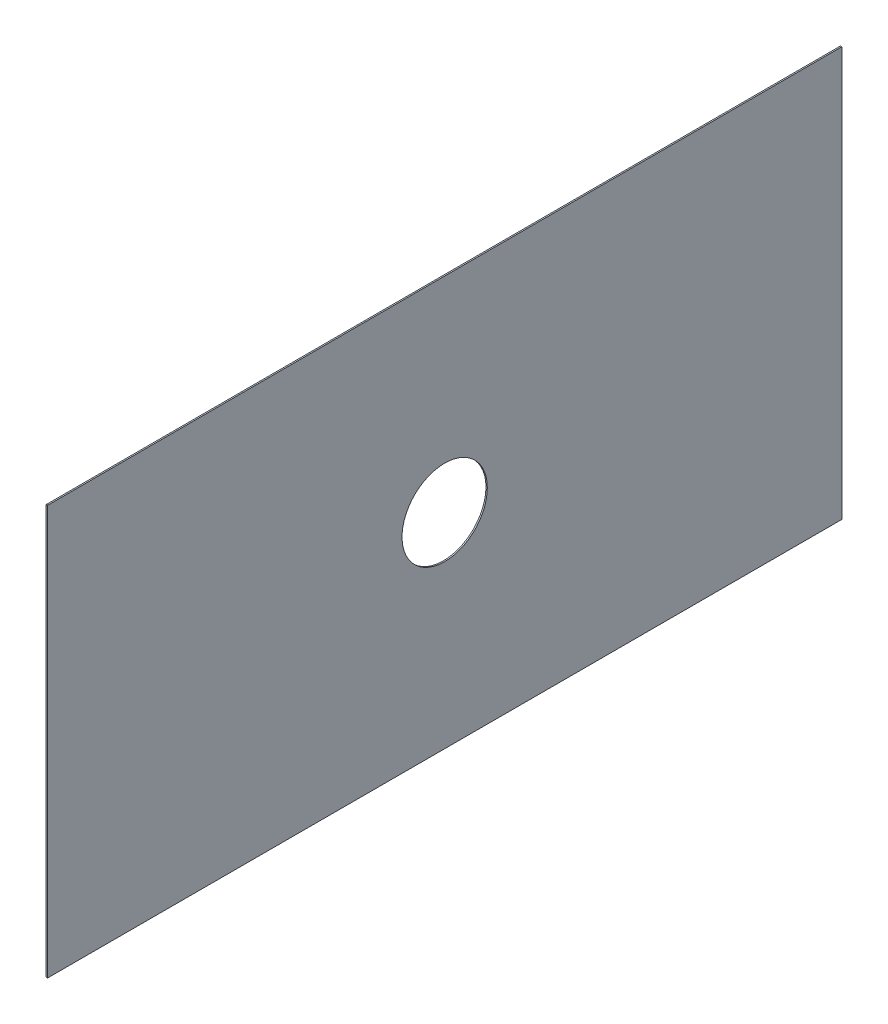
SolidWorks part; units mm, degrees
ref_plane "Alzado" through (0, 0, 0) normal (0, 0, 1) x (1, 0, 0)
ref_plane "Planta" through (0, 0, 0) normal (0, 1, 0) x (1, 0, 0)
ref_plane "Vista lateral" through (0, 0, 0) normal (1, 0, 0) x (0, 0, -1)
sketch "Croquis1" plane through (0, 0, 0) normal (1, 0, 0) x (0, 0, -1)
  line L1 (582, -300) -> (-582, -300)
  line L2 (582, -300) -> (582, 300)
  line L3 (582, 300) -> (-582, 300)
  line L4 (-582, -300) -> (-582, 300)
  line L5 (582, -300) -> (-582, 300) construction
  line L6 (582, 300) -> (-582, -300) construction
  point P0 (0, 0)
  dimension "D1" = 600
  dimension "D2" = 1164
extrude "Extruir1" add sketch "Croquis1" along normal blind 2
sketch "Croquis2" plane through (2, 0, 0) normal (1, 0, 0) x (0, 0, -1)
  circle A0 centre (0, 0) radius 62.5
  dimension "D1" = 125
extrude "Extruir2" cut sketch "Croquis2" against normal blind 2
